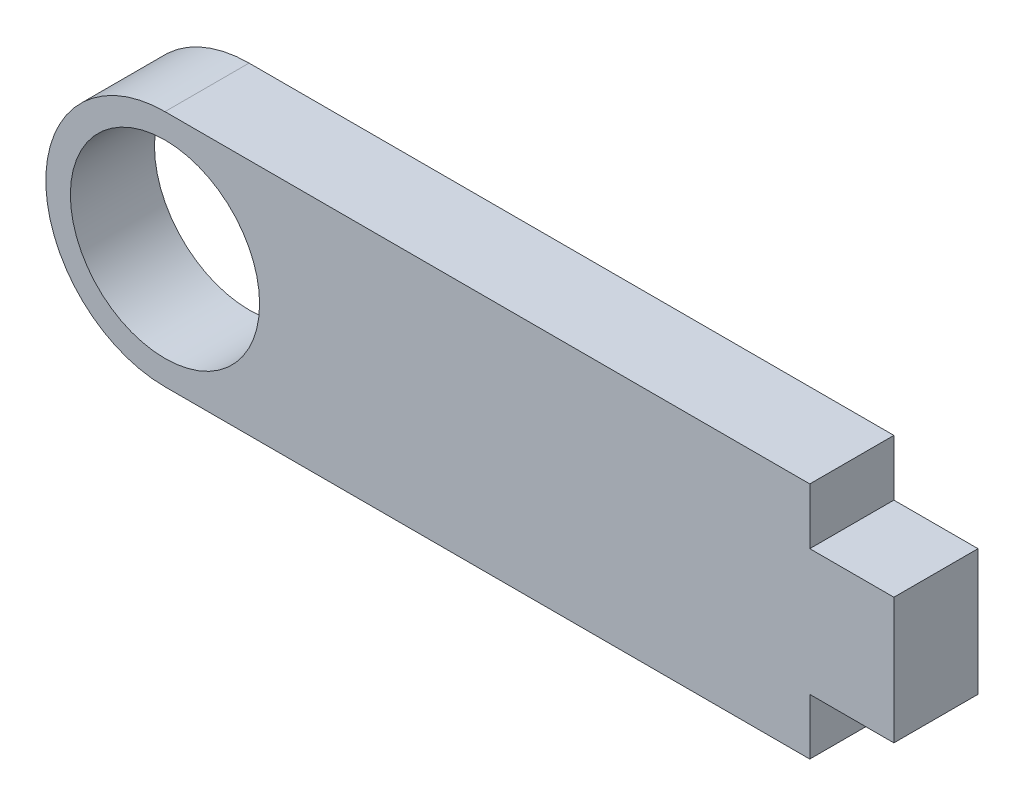
SolidWorks part; units mm, degrees
ref_plane "Alzado" through (0, 0, 0) normal (0, 0, 1) x (1, 0, 0)
ref_plane "Planta" through (0, 0, 0) normal (0, 1, 0) x (1, 0, 0)
ref_plane "Vista lateral" through (0, 0, 0) normal (1, 0, 0) x (0, 0, -1)
sketch "Croquis1" plane through (0, 0, 0) normal (0, 0, 1) x (1, 0, 0)
  line L0 (-26, 4.25) -> (-3, 4.25)
  line L2 (-26, 12.75) -> (-3, 12.75)
  line L3 (-3, 12.75) -> (-3, 10.75)
  line L4 (-3, 10.75) -> (0, 10.75)
  line L6 (0, 10.75) -> (0, 6.25)
  line L7 (0, 6.25) -> (-3, 6.25)
  line L8 (-3, 6.25) -> (-3, 4.25)
  circle A0 centre (-26, 8.5) radius 3.375
  arc A1 (-26, 12.75) -> (-26, 4.25) centre (-26, 8.5) ccw
  dimension "D1" = 6.75
  dimension "D2" = 8.5
  dimension "D3" = 2
extrude "Saliente-Extruir1" add sketch "Croquis1" along normal blind 3
